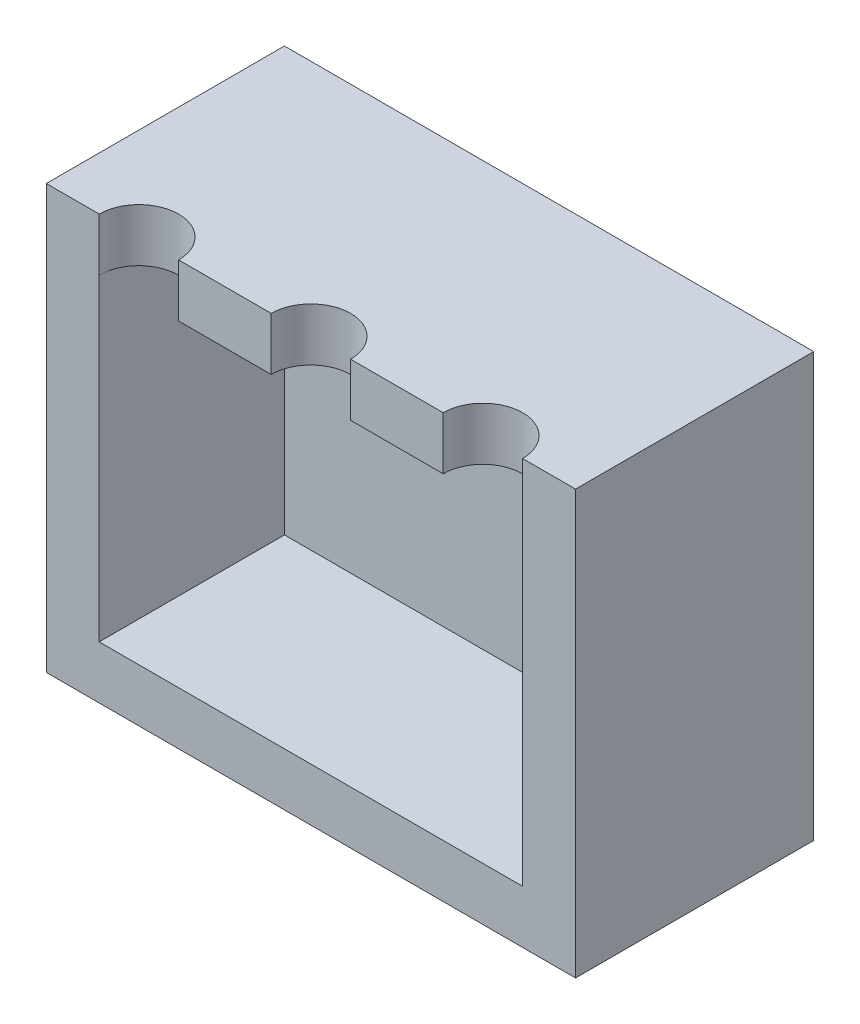
SolidWorks part; units mm, degrees
ref_plane "Front Plane" through (0, 0, 0) normal (0, 0, 1) x (1, 0, 0)
ref_plane "Top Plane" through (0, 0, 0) normal (0, 1, 0) x (1, 0, 0)
ref_plane "Right Plane" through (0, 0, 0) normal (1, 0, 0) x (0, 0, -1)
sketch "Sketch1" plane through (0, 0, 0) normal (0, 0, 1) x (1, 0, 0)
  line L1 (0, 0) -> (20, 0)
  line L2 (0, 0) -> (0, 16)
  line L3 (0, 16) -> (20, 16)
  line L4 (20, 0) -> (20, 16)
  dimension "D1" = 20
  dimension "D2" = 16
extrude "Boss-Extrude1" add sketch "Sketch1" along normal blind 9
sketch "Sketch2" plane through (0, 0, 9) normal (0, 0, 1) x (1, 0, 0)
  line L0 (0, 16) -> (0, 0) construction
  line L1 (2, 14) -> (18, 14)
  line L2 (2, 14) -> (2, 2)
  line L3 (2, 2) -> (18, 2)
  line L4 (18, 14) -> (18, 2)
  line L5 (20, 0) -> (20, 16) construction
  line L6 (20, 16) -> (0, 16) construction
  line L7 (0, 0) -> (20, 0) construction
  dimension "D1" = 2
  dimension "D2" = 2
  dimension "D3" = 2
  dimension "D4" = 2
extrude "Cut-Extrude1" cut sketch "Sketch2" against normal blind 7
sketch "Sketch4" plane through (0, 16, 0) normal (0, 1, 0) x (1, 0, 0)
  line L0 (0, -9) -> (0, 0) construction
  line L1 (20, -9) -> (0, -9) construction
  line L3 (20, -9) -> (20, 0) construction
  circle A0 centre (3.5, -9) radius 1.5
  circle A1 centre (10, -9) radius 1.5
  circle A2 centre (16.5, -9) radius 1.5
  point P10 (0, 0)
  point P12 (20, -8.3773)
  dimension "D1" = 3
  dimension "D2" = 3
  dimension "D3" = 3
  dimension "D4" = 3.5
  dimension "D5" = 0
  dimension "D6" = 0
  dimension "D7" = 0
  dimension "D8" = 3.5
  dimension "D9" = 6.5
extrude "Cut-Extrude3" cut sketch "Sketch4" against normal blind 7
